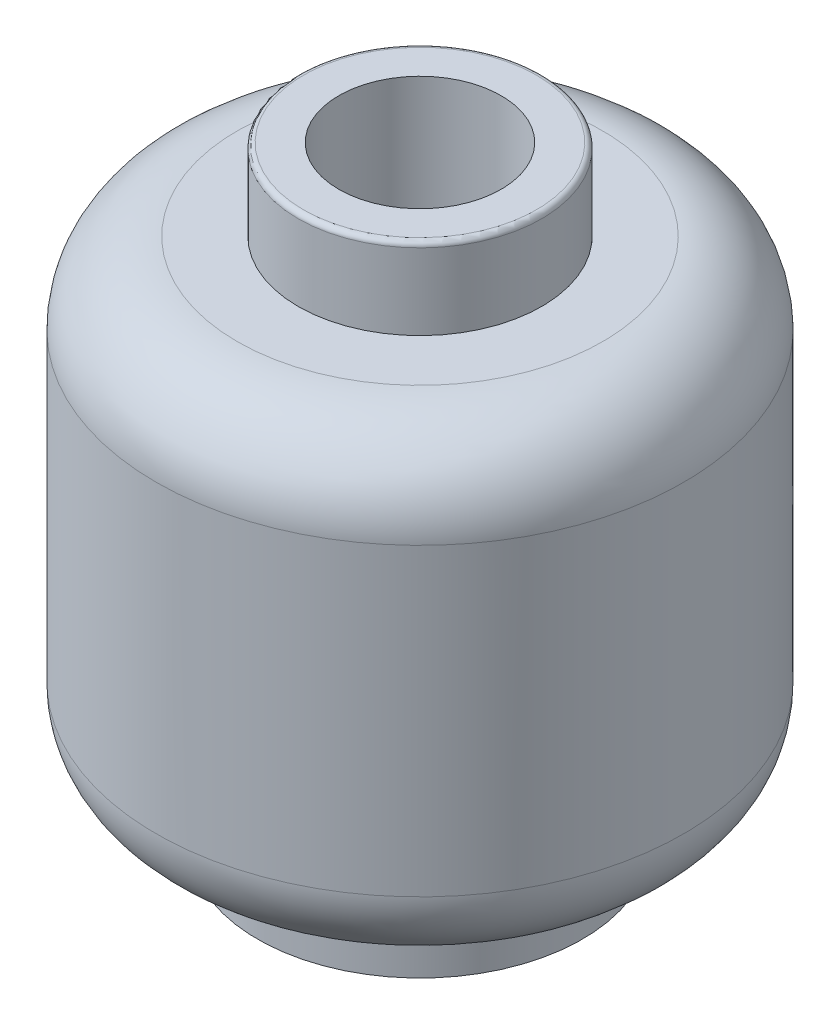
SolidWorks part; units mm, degrees
material "ABS"
ref_plane "Front Plane" through (0, 0, 0) normal (0, 0, 1) x (1, 0, 0)
ref_plane "Top Plane" through (0, 0, 0) normal (0, 1, 0) x (1, 0, 0)
ref_plane "Right Plane" through (0, 0, 0) normal (1, 0, 0) x (0, 0, -1)
sketch "Sketch2" plane through (0, 0, 0) normal (0, 1, 0) x (1, 0, 0)
  circle A0 centre (5.1594, 5.1594) radius 5.1594
  dimension "D1" = 10.3187
  dimension "D2" = 5.1594
  dimension "D3" = 5.1594
extrude "Boss-Extrude2" add sketch "Sketch2" along normal blind 11.9062
sketch "Sketch3" plane through (0, 11.9062, 0) normal (0, 1, 0) x (1, 0, 0)
  circle A0 centre (5.1594, 5.1594) radius 2.3813
  circle A1 centre (5.1594, 5.1594) radius 5.1594
  circle A2 centre (5.1594, 5.1594) radius 5.1594 construction
  dimension "D1" = 4.7625
extrude "Cut-Extrude1" cut sketch "Sketch3" against normal blind 1.5875
sketch "Sketch4" plane through (0, 0, 0) normal (0, -1, 0) x (1, 0, 0)
  circle A0 centre (5.1594, -5.1594) radius 5.1594
  circle A1 centre (5.1594, -5.1594) radius 3.175
  dimension "D1" = 6.35
extrude "Cut-Extrude2" cut sketch "Sketch4" against normal blind 1.1906
sketch "Sketch5" plane through (0, 0, 0) normal (0, -1, 0) x (1, 0, 0)
  circle A0 centre (5.1594, -5.1594) radius 2.3813
  dimension "D1" = 4.7625
extrude "Cut-Extrude3" cut sketch "Sketch5" against normal blind 8.7312
sketch "Sketch6" plane through (0, 11.9062, 0) normal (0, 1, 0) x (1, 0, 0)
  circle A0 centre (5.1594, 5.1594) radius 1.5875
  dimension "D1" = 3.175
extrude "Cut-Extrude4" cut sketch "Sketch6" against normal blind 2.3813
fillet "Fillet1" radius 1.5875 2 edges at (5.1594, 1.1906, -10.3188) (5.1594, 10.3187, 0)
fillet "Fillet3" radius 0.1016 1 edges at (5.1594, 11.9062, -2.7781)
